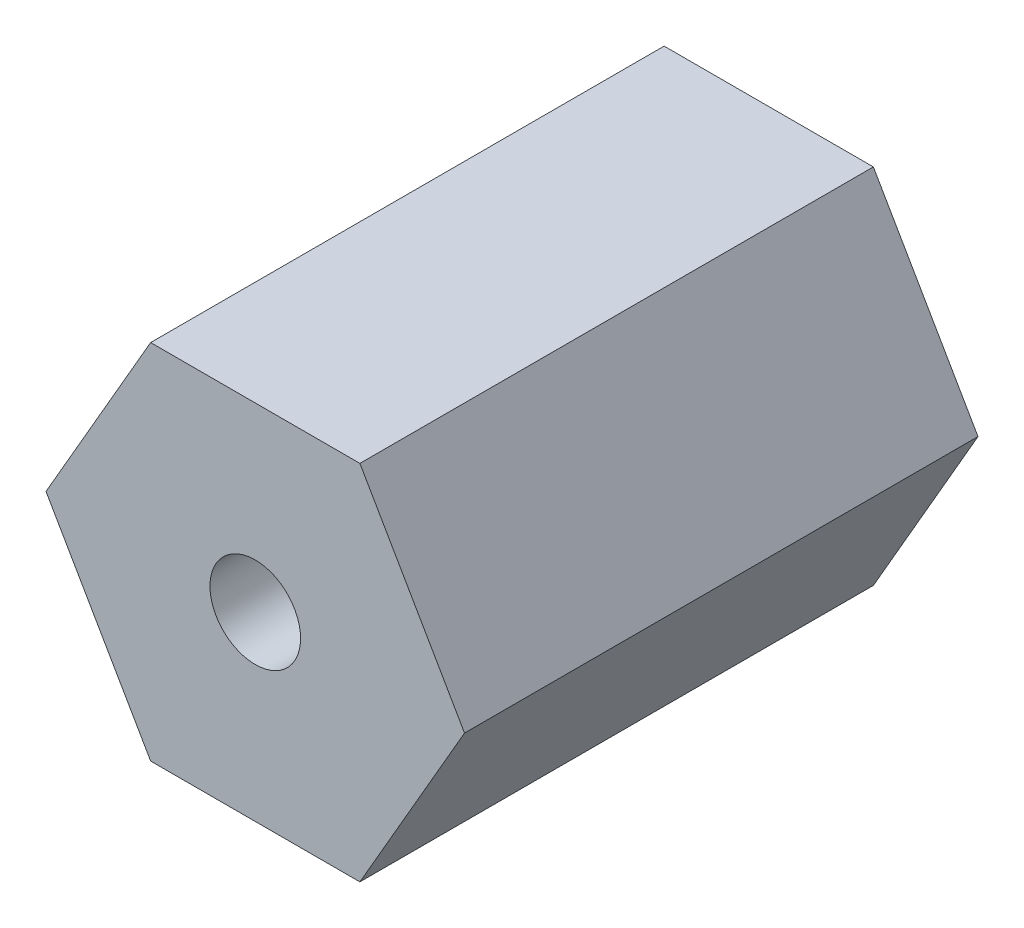
SolidWorks part; units mm, degrees
ref_plane "Front Plane" through (0, 0, 0) normal (0, 0, 1) x (1, 0, 0)
ref_plane "Top Plane" through (0, 0, 0) normal (0, 1, 0) x (1, 0, 0)
ref_plane "Right Plane" through (0, 0, 0) normal (1, 0, 0) x (0, 0, -1)
sketch "Sketch1" plane through (0, 0, 0) normal (0, 0, 1) x (1, 0, 0)
  line L1 (6.9282, 0) -> (3.4641, 6)
  line L2 (3.4641, 6) -> (-3.4641, 6)
  line L3 (-3.4641, 6) -> (-6.9282, 0)
  line L4 (-6.9282, 0) -> (-3.4641, -6)
  line L5 (-3.4641, -6) -> (3.4641, -6)
  line L6 (3.4641, -6) -> (6.9282, 0)
  circle A0 centre (0, 0) radius 1.5
  circle A1 centre (0, 0) radius 6 construction
  dimension "D1" = 3
  dimension "D2" = 12
extrude "Boss-Extrude1" add sketch "Sketch1" along normal blind 17
